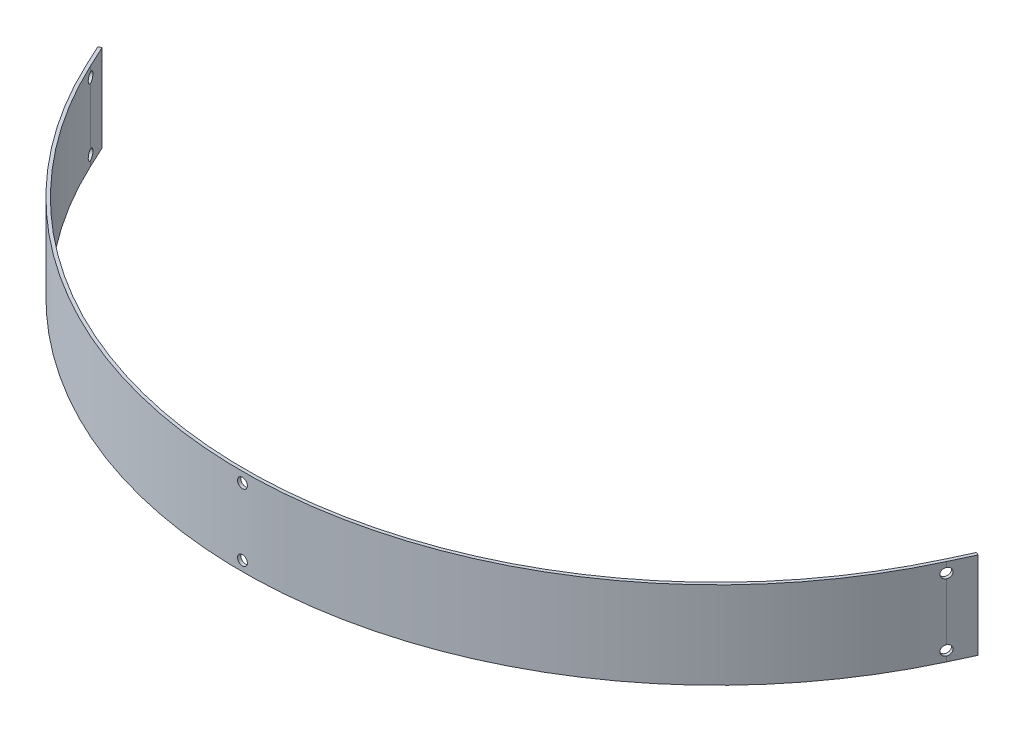
SolidWorks part; units mm, degrees
ref_plane "Front Plane" through (0, 0, 0) normal (0, 0, 1) x (1, 0, 0)
ref_plane "Top Plane" through (0, 0, 0) normal (0, 1, 0) x (1, 0, 0)
ref_plane "Right Plane" through (0, 0, 0) normal (1, 0, 0) x (0, 0, -1)
sketch "Sketch2" plane through (0, 0, 0) normal (1, 0, 0) x (0, 0, -1)
  line L0 (0, 0) -> (-150, 0) construction
  line L1 (-150, 0) -> (-149, 0) construction
  line L2 (0, -1000) -> (0, 49000) construction
  line L3 (-150, 13.75) -> (-149, 13.75)
  line L4 (-150, 13.75) -> (-150, -13.75)
  line L5 (-150, -13.75) -> (-149, -13.75)
  line L6 (-149, 13.75) -> (-149, -13.75)
  point P8 (-149, 0)
  point P9 (-150, 0)
  dimension "D1" = 150
  dimension "D2" = 1
  dimension "D3" = 27.5
revolve "Revolve1" add sketch "Sketch2" angle 130 mid plane about L2
sketch "Sketch3" plane through (0, 0, 0) normal (0.4226, 0, -0.9063) x (-0.9063, 0, -0.4226)
  line L4 (-150, 13.75) -> (-150, -13.75)
  line L5 (-150, -13.75) -> (-149, -13.75)
  line L6 (-149, -13.75) -> (-149, 13.75)
  line L7 (-149, 13.75) -> (-150, 13.75)
  line L8 (-150, 13.75) -> (-150, -13.75)
  line L9 (-150, -13.75) -> (-149, -13.75)
  line L10 (-149, -13.75) -> (-149, 13.75)
  line L11 (-149, 13.75) -> (-150, 13.75)
  dimension "D1" = 0
extrude "Boss-Extrude1" add sketch "Sketch3" along normal blind 7.5
sketch "Sketch4" plane through (0, 0, 0) normal (-0.4226, 0, -0.9063) x (-0.9063, 0, 0.4226)
  line L4 (150, -13.75) -> (150, 13.75)
  line L5 (150, 13.75) -> (149, 13.75)
  line L6 (149, 13.75) -> (149, -13.75)
  line L7 (149, -13.75) -> (150, -13.75)
  line L8 (150, -13.75) -> (150, 13.75)
  line L9 (150, 13.75) -> (149, 13.75)
  line L10 (149, 13.75) -> (149, -13.75)
  line L11 (149, -13.75) -> (150, -13.75)
  dimension "D1" = 0
extrude "Boss-Extrude2" add sketch "Sketch4" along normal blind 7.5
hole_wizard "M2.5 Clearance Hole1" positions "Sketch5" profile "Sketch6" hole size "M2.5" standard "ANSI Metric" end condition through all
sketch "Sketch5" plane through (0, 0, 0) normal (0, 0, 1) x (1, 0, 0)
  line L0 (-135.9462, -13.75) -> (135.9462, -13.75) construction
  line L1 (135.9462, 13.75) -> (-135.9462, 13.75) construction
  point P0 (0, 10.575)
  point P2 (0, -10.575)
  dimension "D1" = 3.175
  dimension "D2" = 3.175
sketch "Sketch6" plane through (0, 10.575, 0) normal (1, 0, 0) x (0, 1, 0)
  line L0 (0, 0) -> (0, 150)
  line L1 (0, 150) -> (1.55, 150)
  line L2 (1.55, 150) -> (1.55, 0)
  line L5 (1.55, 0) -> (0, 0)
  line L11 (0, -6.35) -> (0, 107.95) construction
  dimension "Thru Hole Dia." = 3.1
  dimension "Thru Hole Depth" = 150
pattern_circular "CirPattern1" count 2 every 65 about axis through (0, -1000, 0) along (0, 1, 0) of "M2.5 Clearance Hole1"
